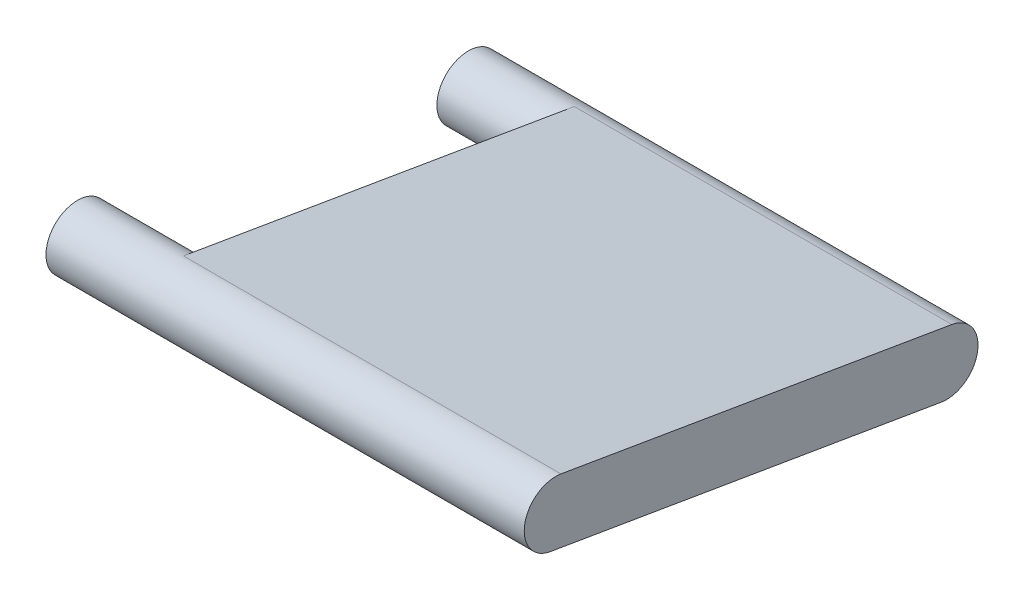
SolidWorks part; units mm, degrees
ref_plane "Front Plane" through (0, 0, 0) normal (0, 0, 1) x (1, 0, 0)
ref_plane "Top Plane" through (0, 0, 0) normal (0, 1, 0) x (1, 0, 0)
ref_plane "Right Plane" through (0, 0, 0) normal (1, 0, 0) x (0, 0, -1)
sketch "Sketch1" plane through (0, 0, 0) normal (1, 0, 0) x (0, 0, -1)
  line L0 (0, 0) -> (39.446, -6.6643) construction
  line L1 (0.5289, 3.1306) -> (39.9749, -3.5337)
  line L2 (-0.5289, -3.1306) -> (38.9171, -9.795)
  arc A0 (0.5289, 3.1306) -> (-0.5289, -3.1306) centre (0, 0) ccw
  arc A1 (38.9171, -9.795) -> (39.9749, -3.5337) centre (39.446, -6.6643) ccw
  point P3 (19.723, -3.3322)
  dimension "D1" = 6.35
  dimension "D2" = 40.005
extrude "Boss-Extrude1" add sketch "Sketch1" along normal blind 38.1
sketch "Sketch2" plane through (0, 0, 0) normal (-1, 0, 0) x (0, 0, 1)
  circle A0 centre (-39.446, -6.6643) radius 3.175
  circle A1 centre (0, 0) radius 3.175
extrude "Boss-Extrude2" add sketch "Sketch2" along normal blind 10.16
